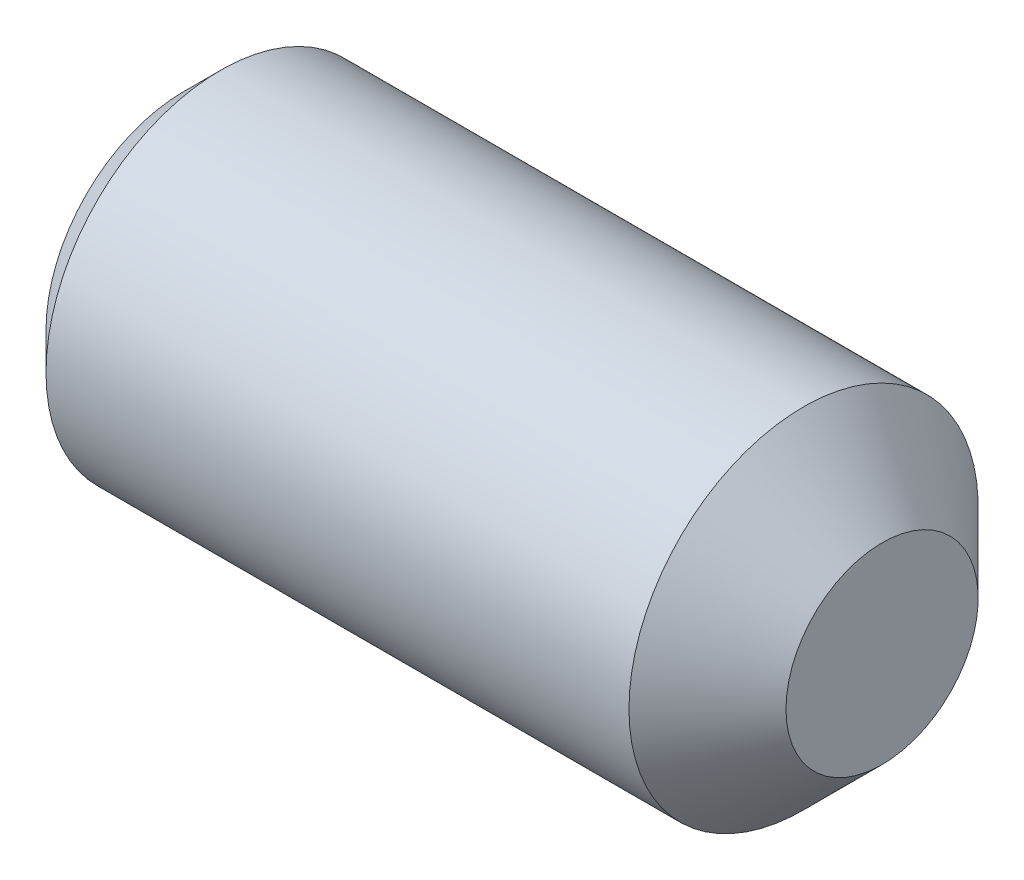
SolidWorks part; units mm, degrees
ref_plane "Plane1" through (0, 0, 0) normal (0, 0, 1) x (1, 0, 0)
ref_plane "Plane2" through (0, 0, 0) normal (0, 1, 0) x (1, 0, 0)
ref_plane "Plane3" through (0, 0, 0) normal (1, 0, 0) x (0, 0, -1)
sketch "BodySke" plane through (0, 0, 0) normal (0, 0, 1) x (1, 0, 0)
  line L0 (0, 0) -> (0, 3.1293)
  line L1 (0, 3.1293) -> (0.8395, 3.9688)
  line L2 (0.8395, 3.9688) -> (14.0907, 3.9688)
  line L3 (14.0907, 3.9688) -> (15.875, 2.1844)
  line L4 (15.875, 0) -> (0, 0)
  line L5 (-12.7, 0) -> (88.9, 0) construction
  line L6 (15.875, 2.1844) -> (15.875, 0)
  line L7 (15.875, 2.1844) -> (15.875, 11.7094) construction
  line L8 (0, -3.1293) -> (0.8395, -3.9688) construction
  line L9 (1.4097, 15.875) -> (1.4097, -3.175) construction
  line L10 (14.0907, -3.9688) -> (15.875, -2.1844) construction
  dimension "Length" = 15.875
  dimension "Diameter" = 7.9375
  dimension "Drive_ch_ang" = 45
  dimension "Minor_dia" = 6.2586
  dimension "Cup_nose_ang" = 45
  dimension "Cup_dia" = 4.3688
  dimension "Advance" = 1.4097
revolve "BaseBody" add sketch "BodySke" angle 360 about L5
cosmetic thread "ThreadCosmetic" [suppressed] parameters "Thread_minor"=6.2586
sketch "Sketch2" plane through (0, 0, 0) normal (-1, 0, 0) x (0, 0, 1)
  line L0 (1.1453, 1.9837) -> (-1.1453, 1.9837)
  line L1 (-1.1453, 1.9837) -> (-2.2906, 0)
  line L2 (1.1453, 1.9837) -> (2.2906, 0)
  line L3 (1.1453, -1.9837) -> (2.2906, 0)
  line L4 (1.1453, -1.9837) -> (-1.1453, -1.9837)
  line L5 (-1.1453, -1.9837) -> (-2.2906, 0)
  dimension "Hex_size" = 3.9675
  dimension "D2" = 1.9837
  dimension "D3" = 1.9837
extrude "Hex" cut sketch "Sketch2" against normal blind 3.9624
sketch "Sketch4" plane through (0, 4.7709, -0.5249) normal (-1, 0, 0) x (0, 0, 1)
  line L0 (0.5249, -4.7709) -> (2.9125, -4.7709)
  line L1 (0.5249, -4.7709) -> (6.6732, -1.2211) construction
  line L2 (0.5249, -4.7709) -> (1.7187, -2.7032)
  line L3 (2.5132, -4.1948) -> (2.7953, -4.032)
  line L4 (2.0179, -3.3369) -> (2.3, -3.1741)
  arc A0 (2.5132, -4.1948) -> (2.0179, -3.3369) centre (0.5249, -4.7709) ccw
  arc A1 (2.9125, -4.7709) -> (2.7953, -4.032) centre (0.5249, -4.7709) ccw
  arc A2 (1.7187, -2.7032) -> (2.3, -3.1741) centre (0.5249, -4.7709) cw
  circle A3 centre (0.5249, -4.7709) radius 2.0701 construction
  circle A4 centre (0.5249, -4.7709) radius 2.3876 construction
  dimension "D1" = 30
  dimension "Spline_n_dim" = 4.1402
  dimension "Spline_m_dim" = 4.7752
  dimension "Spline_a_dim" = 60
  dimension "D3" = 0.4953
  dimension "Spline_p_dim" = 0.9906
extrude "Spline" [suppressed] cut sketch "Sketch4" against normal blind 3.9624
pattern_circular "CirPattern1" [suppressed] count 6 every 60 about axis through (-12.7, 0, 0) along (1, 0, 0)
sketch "ThdSchSke" plane through (0, 0, 0) normal (0, 0, 1) x (1, 0, 0)
  line L0 (0.8395, -3.1293) -> (0.2517, -3.9688)
  line L1 (0.8395, -3.1293) -> (1.4273, -3.9688)
  line L2 (1.4273, -3.9688) -> (1.4273, -4.9609)
  line L3 (-3.175, 0) -> (5.1513, 0) construction
  line L4 (0.8395, 3.9688) -> (0.8395, -3.9688) construction
  line L5 (1.4273, -4.9609) -> (0.2517, -4.9609)
  line L6 (0.2517, -4.9609) -> (0.2517, -3.9688)
  dimension "Thread_minor" = 6.2586
  dimension "Diameter" = 7.9375
  dimension "SideAngle" = 55
  dimension "VeeAngle" = 70
  dimension "Overcut" = 9.9219
revolve "ThreadSchematic" [suppressed] cut sketch "ThdSchSke" angle 360 about L3
pattern_linear "ThdSchPat" [suppressed]
equation "\"D2@Sketch2\" = \"Hex_size@Sketch2\" / 2"
equation "\"D3@Sketch2\" = \"Hex_size@Sketch2\" / 2"
equation "\"Thread_minor@ThreadCosmetic\" = \"Minor_dia@BodySke\""
equation "\"D1@Sketch4\" = \"Spline_a_dim@Sketch4\" / 2"
equation "\"D3@Sketch4\" = \"Spline_p_dim@Sketch4\" / 2"
equation "\"D2@CirPattern1\" = \"Spline_a_dim@Sketch4\""
equation "\"Num_teeth@CirPattern1\" = 360 / \"D2@CirPattern1\""
equation "\"Thread_minor@ThdSchSke\" = \"Thread_minor@ThreadCosmetic\""
equation "\"Diameter@ThdSchSke\" = \"Diameter@BodySke\""
equation "\"Overcut@ThdSchSke\" = \"Diameter@BodySke\" * 1.25"
equation "\"Num_threads@ThdSchPat\" = int( (\"Length@BodySke\" - ( ( ( \"Diameter@BodySke\" - \"Minor_dia@BodySke\" ) * 0.5 ) / tan( \"Drive_ch_ang@BodySke\" * 0.017453292 ) ) - ( ( ( \"Diameter@BodySke\" - \"Cup_dia@BodySke\" ) * 0.5 ) * tan( \"Cup_nose_ang@BodySke\" * 0.017453292 ) ) ) / \"Advance@BodySke\" + 0.999 )  + 1"
equation "\"Advance@ThdSchPat\" = (\"Length@BodySke\" - ( ( ( \"Diameter@BodySke\" - \"Minor_dia@BodySke\" ) * 0.5 ) / tan( \"Drive_ch_ang@BodySke\" * 0.017453292 ) ) - ( ( ( \"Diameter@BodySke\" - \"Cup_dia@BodySke\" ) * 0.5 ) * tan( \"Cup_nose_ang@BodySke\" * 0.017453292 ) ) ) /  (\"Num_threads@ThdSchPat\" - 1) 'relax it"
equation "' \"Num_threads@ThdSchPat\" = \"Num_threads@ThdSchPat\" - sgn( \"Num_threads@ThdSchPat\" - 1) '---chamfered tips only---"
